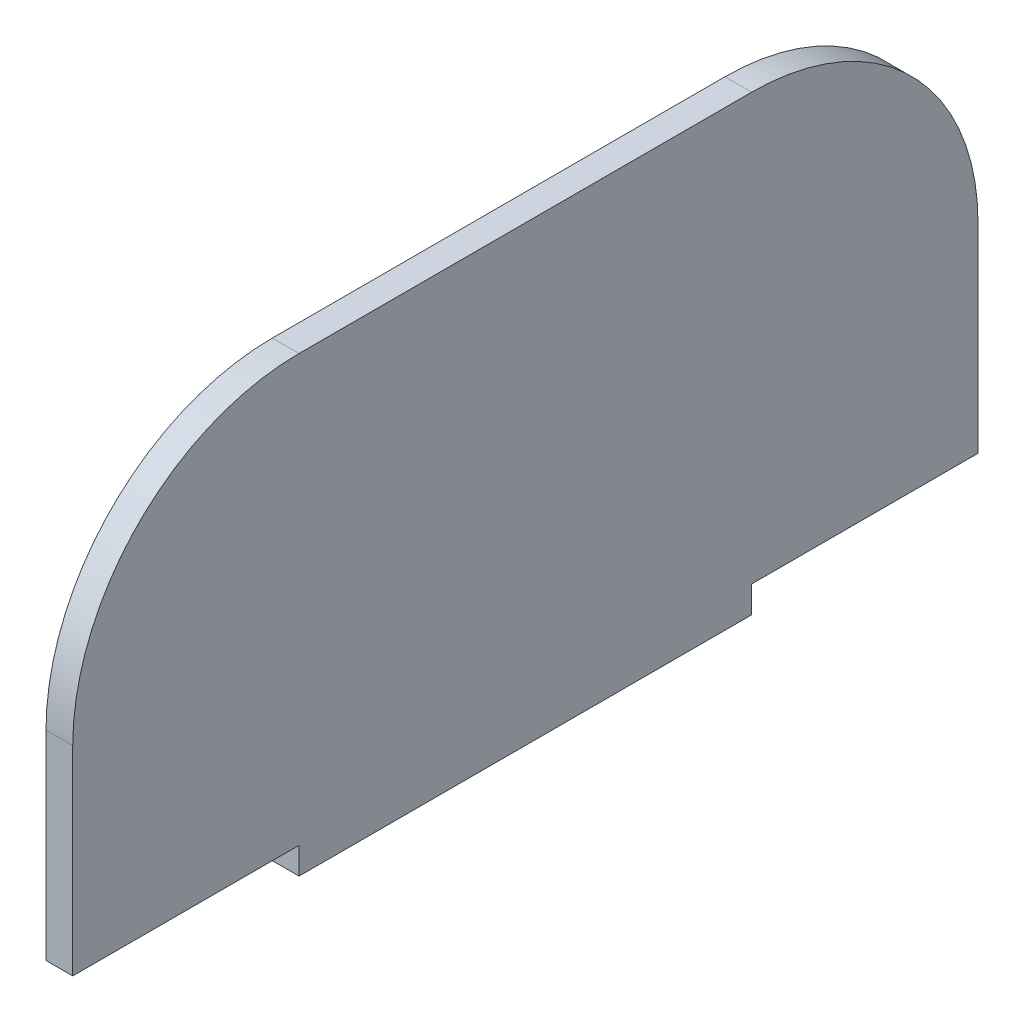
SolidWorks part; units mm, degrees
ref_plane "Front Plane" through (0, 0, 0) normal (0, 0, 1) x (1, 0, 0)
ref_plane "Top Plane" through (0, 0, 0) normal (0, 1, 0) x (1, 0, 0)
ref_plane "Right Plane" through (0, 0, 0) normal (1, 0, 0) x (0, 0, -1)
sketch "Sketch2" plane through (0, 0, 0) normal (1, 0, 0) x (0, 0, -1)
  line L1 (0, 0) -> (101.6, 0)
  line L2 (0, 0) -> (0, 50.8)
  line L3 (0, 50.8) -> (101.6, 50.8)
  line L4 (101.6, 0) -> (101.6, 50.8)
  dimension "D1" = 50.8
  dimension "D2" = 101.6
extrude "Boss-Extrude1" add sketch "Sketch2" along normal blind 3
fillet "Fillet1" radius 25.4 2 edges at (1.5, 50.8, -101.6) (1.5, 50.8, 0)
sketch "Sketch4" plane through (3, 0, 0) normal (1, 0, 0) x (0, 0, -1)
  line L1 (0, 0) -> (25.4, 0)
  line L2 (0, 0) -> (0, 3)
  line L3 (0, 3) -> (25.4, 3)
  line L4 (25.4, 0) -> (25.4, 3)
  line L5 (101.6, 0) -> (76.2, 0)
  line L6 (101.6, 0) -> (101.6, 3)
  line L7 (101.6, 3) -> (76.2, 3)
  line L8 (76.2, 0) -> (76.2, 3)
  dimension "D1" = 3
  dimension "D2" = 3
  dimension "D3" = 25.4
extrude "Cut-Extrude1" cut sketch "Sketch4" against normal blind 3
